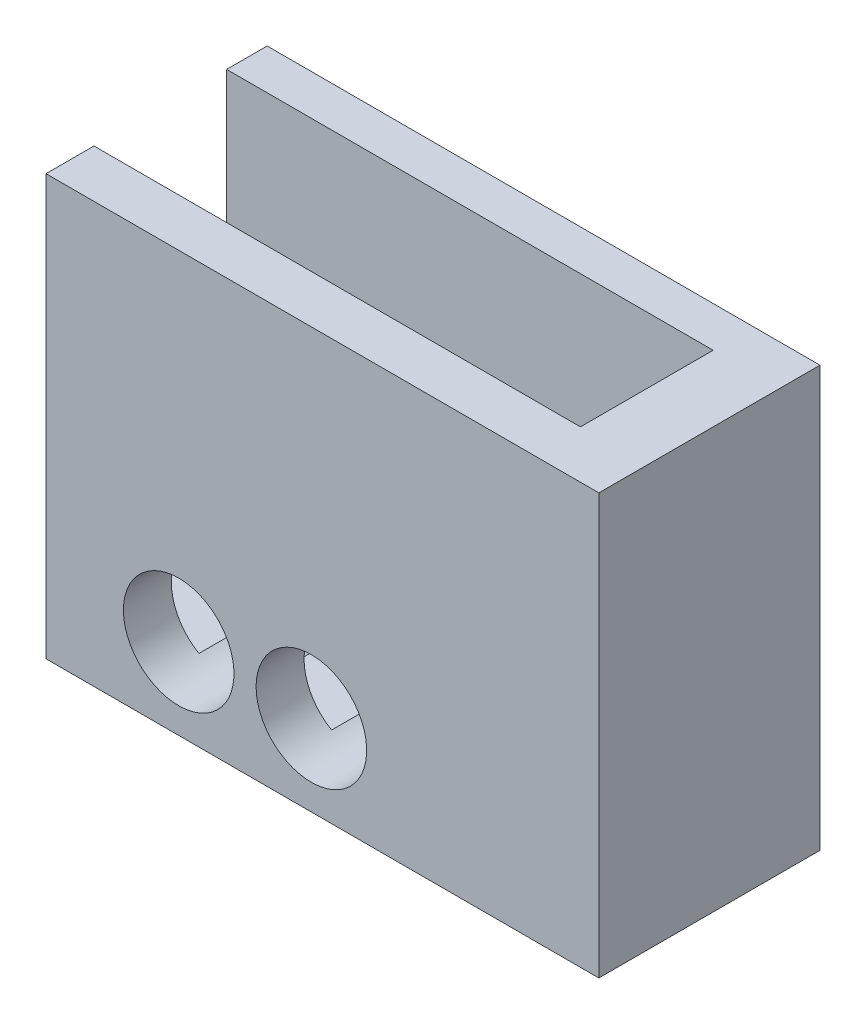
SolidWorks part; units mm, degrees
ref_plane "前基準面" through (0, 0, 0) normal (0, 0, 1) x (1, 0, 0)
ref_plane "上基準面" through (0, 0, 0) normal (0, 1, 0) x (1, 0, 0)
ref_plane "右基準面" through (0, 0, 0) normal (1, 0, 0) x (0, 0, -1)
sketch "草圖1" plane through (0, 0, 0) normal (0, 1, 0) x (1, 0, 0)
  line L1 (-7.2917, 6.1625) -> (17.7083, 6.1625)
  line L2 (-7.2917, 6.1625) -> (-7.2917, -3.8375)
  line L3 (-7.2917, -3.8375) -> (17.7083, -3.8375)
  line L4 (17.7083, 6.1625) -> (17.7083, -3.8375)
  line L5 (-7.2917, 6.1625) -> (17.7083, -3.8375) construction
  line L6 (-7.2917, -3.8375) -> (17.7083, 6.1625) construction
  point P4 (5.2083, 1.1625)
  dimension "D1" = 25
  dimension "D2" = 10
extrude "填料-伸長2" add sketch "草圖1" along normal blind 19
sketch "草圖2" plane through (0, 19, 0) normal (0, 1, 0) x (1, 0, 0)
  line L0 (-7.2917, 6.1625) -> (-7.2917, -3.8375) construction
  line L1 (-7.2917, 4.3309) -> (14.7083, 4.3309)
  line L2 (-7.2917, 4.3309) -> (-7.2917, -1.6691)
  line L3 (-7.2917, -1.6691) -> (14.7083, -1.6691)
  line L4 (14.7083, 4.3309) -> (14.7083, -1.6691)
  line M5 (-7.2917, 6.1625) -> (-7.2917, -3.8375)
  dimension "D1" = 22
  dimension "D2" = 6
extrude "除料-伸長1" cut sketch "草圖2" against normal blind 17.5 contours L4 L1 L3 M5
sketch "草圖3" plane through (0, 0, -6.1625) normal (0, 0, -1) x (-1, 0, 0)
  line L2 (-17.7083, 19) -> (-17.7083, 0) construction
  circle A0 centre (-4.7083, 3.6632) radius 2.5
  circle A1 centre (1.2917, 3.6632) radius 2.5
  dimension "D1" = 5
  dimension "D2" = 5
  dimension "D3" = 13
  dimension "D4" = 6
extrude "除料-伸長2" cut sketch "草圖3" against normal blind 20 contours A0 | A1
